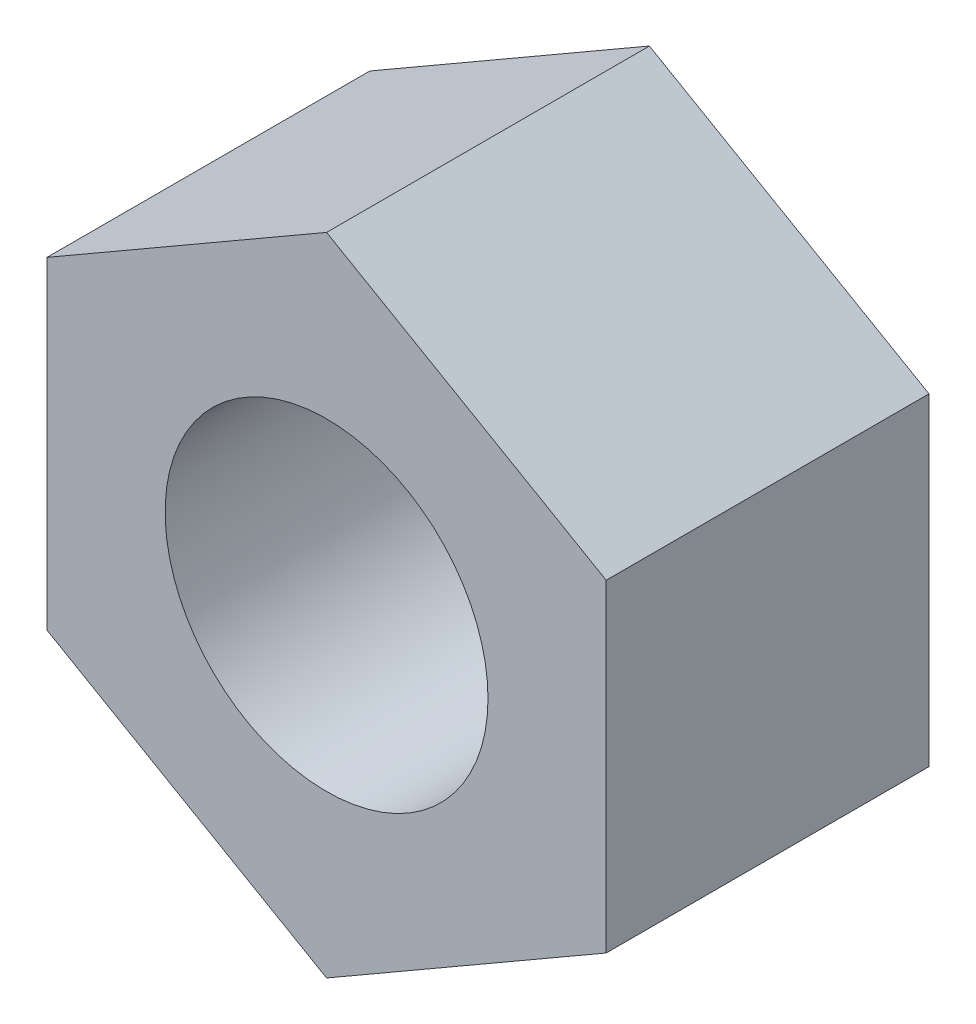
SolidWorks part; units mm, degrees
ref_plane "Front Plane" through (0, 0, 0) normal (0, 0, 1) x (1, 0, 0)
ref_plane "Top Plane" through (0, 0, 0) normal (0, 1, 0) x (1, 0, 0)
ref_plane "Right Plane" through (0, 0, 0) normal (1, 0, 0) x (0, 0, -1)
sketch "Sketch1" plane through (0, 0, 0) normal (0, 0, 1) x (1, 0, 0)
  line L1 (8.6603, 5) -> (0, 10)
  line L2 (0, 10) -> (-8.6603, 5)
  line L3 (-8.6603, 5) -> (-8.6603, -5)
  line L4 (-8.6603, -5) -> (0, -10)
  line L5 (0, -10) -> (8.6603, -5)
  line L6 (8.6603, -5) -> (8.6603, 5)
  circle A0 centre (0, 0) radius 8.6603 construction
  circle A1 centre (0, 0) radius 5
  dimension "D2" = 10
  dimension "D1" = 0
  dimension "D3" = 20
extrude "Boss-Extrude1" add sketch "Sketch1" along normal blind 10
